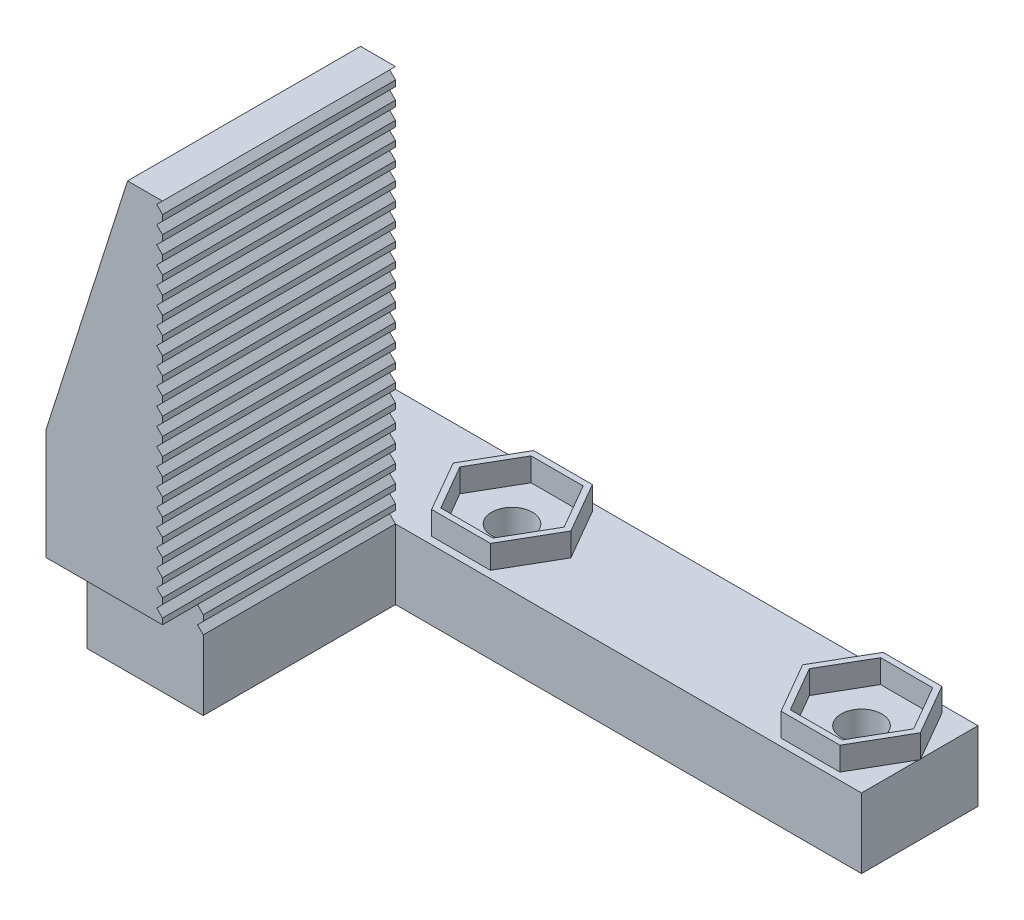
SolidWorks part; units mm, degrees
ref_plane "Front Plane" through (0, 0, 0) normal (0, 0, 1) x (1, 0, 0)
ref_plane "Top Plane" through (0, 0, 0) normal (0, 1, 0) x (1, 0, 0)
ref_plane "Right Plane" through (0, 0, 0) normal (1, 0, 0) x (0, 0, -1)
sketch "Sketch1" plane through (0, 0, 0) normal (0, 0, 1) x (1, 0, 0)
  line L0 (0, 0) -> (0, 40)
  line L1 (0, 40) -> (-3, 40)
  line L2 (-3, 40) -> (-10, 18)
  line L3 (-10, 18) -> (-10, 0)
  line L4 (-10, 0) -> (0, 0)
  dimension "D1" = 40
  dimension "D2" = 10
  dimension "D3" = 22
  dimension "D4" = 3
extrude "Boss-Extrude1" add sketch "Sketch1" along normal blind 20
sketch "Sketch2" plane through (0, 0, 0) normal (0, -1, 0) x (1, 0, 0)
  line L0 (-10, 0) -> (-10, -10)
  line L1 (-10, -10) -> (40, -10)
  line L2 (40, -10) -> (40, 0)
  line L3 (40, 0) -> (0, 0)
  line L5 (0, 0) -> (-10, 0)
  circle A0 centre (35, -5) radius 1.75
  circle A1 centre (5, -5) radius 1.75
  point P12 (40, -5)
  point P13 (0, 0)
  point P14 (0, 0)
  dimension "D6" = 3.5
  dimension "D1" = 10
  dimension "D2" = 30
  dimension "D3" = 50
  dimension "D4" = 5
extrude "Boss-Extrude2" add sketch "Sketch2" against normal blind 6
sketch "Sketch3" plane through (0, 0, 20) normal (0, 0, 1) x (1, 0, 0)
  line L0 (0, 6) -> (-0.5, 6.5)
  line L1 (0, 0) -> (0, 40) construction
  line L2 (-0.5, 6.5) -> (0, 7)
  line L3 (0, 7) -> (0, 6)
  line L4 (0, 6.5) -> (-0.5, 6.5) construction
  line L5 (40, 6) -> (0, 6) construction
  line L6 (0, 7.5) -> (-0.5, 8)
  line L7 (-0.5, 8) -> (0, 8.5)
  line L8 (0, 8.5) -> (0, 7.5)
  line L9 (0, 8) -> (-0.5, 8) construction
  line L10 (0, 9) -> (-0.5, 9.5)
  line L11 (-0.5, 9.5) -> (0, 10)
  line L12 (0, 10) -> (0, 9)
  line L13 (0, 9.5) -> (-0.5, 9.5) construction
  line L14 (0, 10.5) -> (-0.5, 11)
  line L15 (-0.5, 11) -> (0, 11.5)
  line L16 (0, 11.5) -> (0, 10.5)
  line L17 (0, 11) -> (-0.5, 11) construction
  line L18 (0, 12) -> (-0.5, 12.5)
  line L19 (-0.5, 12.5) -> (0, 13)
  line L20 (0, 13) -> (0, 12)
  line L21 (0, 12.5) -> (-0.5, 12.5) construction
  line L22 (0, 13.5) -> (-0.5, 14)
  line L23 (-0.5, 14) -> (0, 14.5)
  line L24 (0, 14.5) -> (0, 13.5)
  line L25 (0, 14) -> (-0.5, 14) construction
  line L26 (0, 15) -> (-0.5, 15.5)
  line L27 (-0.5, 15.5) -> (0, 16)
  line L28 (0, 16) -> (0, 15)
  line L29 (0, 15.5) -> (-0.5, 15.5) construction
  line L30 (0, 16.5) -> (-0.5, 17)
  line L31 (-0.5, 17) -> (0, 17.5)
  line L32 (0, 17.5) -> (0, 16.5)
  line L33 (0, 17) -> (-0.5, 17) construction
  line L34 (0, 18) -> (-0.5, 18.5)
  line L35 (-0.5, 18.5) -> (0, 19)
  line L36 (0, 19) -> (0, 18)
  line L37 (0, 18.5) -> (-0.5, 18.5) construction
  line L38 (0, 19.5) -> (-0.5, 20)
  line L39 (-0.5, 20) -> (0, 20.5)
  line L40 (0, 20.5) -> (0, 19.5)
  line L41 (0, 20) -> (-0.5, 20) construction
  line L42 (0, 21) -> (-0.5, 21.5)
  line L43 (-0.5, 21.5) -> (0, 22)
  line L44 (0, 22) -> (0, 21)
  line L45 (0, 21.5) -> (-0.5, 21.5) construction
  line L46 (0, 22.5) -> (-0.5, 23)
  line L47 (-0.5, 23) -> (0, 23.5)
  line L48 (0, 23.5) -> (0, 22.5)
  line L49 (0, 23) -> (-0.5, 23) construction
  line L50 (0, 24) -> (-0.5, 24.5)
  line L51 (-0.5, 24.5) -> (0, 25)
  line L52 (0, 25) -> (0, 24)
  line L53 (0, 24.5) -> (-0.5, 24.5) construction
  line L54 (0, 25.5) -> (-0.5, 26)
  line L55 (-0.5, 26) -> (0, 26.5)
  line L56 (0, 26.5) -> (0, 25.5)
  line L57 (0, 26) -> (-0.5, 26) construction
  line L58 (0, 27) -> (-0.5, 27.5)
  line L59 (-0.5, 27.5) -> (0, 28)
  line L60 (0, 28) -> (0, 27)
  line L61 (0, 27.5) -> (-0.5, 27.5) construction
  line L62 (0, 28.5) -> (-0.5, 29)
  line L63 (-0.5, 29) -> (0, 29.5)
  line L64 (0, 29.5) -> (0, 28.5)
  line L65 (0, 29) -> (-0.5, 29) construction
  line L66 (0, 30) -> (-0.5, 30.5)
  line L67 (-0.5, 30.5) -> (0, 31)
  line L68 (0, 31) -> (0, 30)
  line L69 (0, 30.5) -> (-0.5, 30.5) construction
  line L70 (0, 31.5) -> (-0.5, 32)
  line L71 (-0.5, 32) -> (0, 32.5)
  line L72 (0, 32.5) -> (0, 31.5)
  line L73 (0, 32) -> (-0.5, 32) construction
  line L74 (0, 33) -> (-0.5, 33.5)
  line L75 (-0.5, 33.5) -> (0, 34)
  line L76 (0, 34) -> (0, 33)
  line L77 (0, 33.5) -> (-0.5, 33.5) construction
  line L78 (0, 34.5) -> (-0.5, 35)
  line L79 (-0.5, 35) -> (0, 35.5)
  line L80 (0, 35.5) -> (0, 34.5)
  line L81 (0, 35) -> (-0.5, 35) construction
  line L82 (0, 36) -> (-0.5, 36.5)
  line L83 (-0.5, 36.5) -> (0, 37)
  line L84 (0, 37) -> (0, 36)
  line L85 (0, 36.5) -> (-0.5, 36.5) construction
  line L86 (0, 37.5) -> (-0.5, 38)
  line L87 (-0.5, 38) -> (0, 38.5)
  line L88 (0, 38.5) -> (0, 37.5)
  line L89 (0, 38) -> (-0.5, 38) construction
  line L90 (0, 39) -> (-0.5, 39.5)
  line L91 (-0.5, 39.5) -> (0, 40)
  line L92 (0, 40) -> (0, 39)
  line L93 (0, 39.5) -> (-0.5, 39.5) construction
  line L94 (0, 40.5) -> (-0.5, 41)
  line L95 (-0.5, 41) -> (0, 41.5)
  line L96 (0, 41.5) -> (0, 40.5)
  line L97 (0, 41) -> (-0.5, 41) construction
  dimension "D1" = 0.5
  dimension "D2" = 1
  dimension "D4" = 1.5
  dimension "D3" = 24
extrude "Cut-Extrude1" cut sketch "Sketch3" against normal blind 20
sketch "Sketch4" plane through (0, 6, 0) normal (0, 1, 0) x (1, 0, 0)
  line L0 (39.4745, 5) -> (37.2372, 8.875)
  line L1 (9.4745, 5) -> (7.2372, 8.875)
  line L2 (7.2372, 8.875) -> (2.7628, 8.875)
  line L3 (2.7628, 8.875) -> (0.5255, 5)
  line L4 (0.5255, 5) -> (2.7628, 1.125)
  line L5 (2.7628, 1.125) -> (7.2372, 1.125)
  line L6 (7.2372, 1.125) -> (9.4745, 5)
  line L7 (10.0518, 5) -> (7.5259, 9.375)
  line L8 (7.5259, 9.375) -> (2.4741, 9.375)
  line L9 (2.4741, 9.375) -> (-0.0518, 5)
  line L10 (-0.0518, 5) -> (2.4741, 0.625)
  line L11 (2.4741, 0.625) -> (7.5259, 0.625)
  line L12 (7.5259, 0.625) -> (10.0518, 5)
  line L13 (37.2372, 8.875) -> (32.7628, 8.875)
  line L14 (32.7628, 8.875) -> (30.5255, 5)
  line L15 (30.5255, 5) -> (32.7628, 1.125)
  line L16 (32.7628, 1.125) -> (37.2372, 1.125)
  line L17 (37.2372, 1.125) -> (39.4745, 5)
  line L18 (40.0518, 5) -> (37.5259, 9.375)
  line L19 (37.5259, 9.375) -> (32.4741, 9.375)
  line L20 (32.4741, 9.375) -> (29.9482, 5)
  line L21 (29.9482, 5) -> (32.4741, 0.625)
  line L22 (32.4741, 0.625) -> (37.5259, 0.625)
  line L23 (37.5259, 0.625) -> (40.0518, 5)
  circle A0 centre (5, 5) radius 3.875 construction
  circle A1 centre (5, 5) radius 4.375 construction
  circle A2 centre (35, 5) radius 3.875 construction
  circle A3 centre (35, 5) radius 4.375 construction
  dimension "D1" = 0.5
  dimension "D2" = 7.75
  dimension "D3" = 2
extrude "Boss-Extrude3" add sketch "Sketch4" along normal blind 2
sketch "Sketch5" plane through (0, 0, 20) normal (0, 0, 1) x (1, 0, 0)
  line L0 (0, 0) -> (0, 6) construction
  line L1 (-10, 0) -> (0, 0)
  line L2 (-10, 0) -> (-10, 8.5)
  line L3 (-10, 8.5) -> (0, 8.5)
  line L4 (0, 0) -> (0, 8.5)
  dimension "D1" = 8.5
extrude "Cut-Extrude2" cut sketch "Sketch5" against normal blind 3.5
